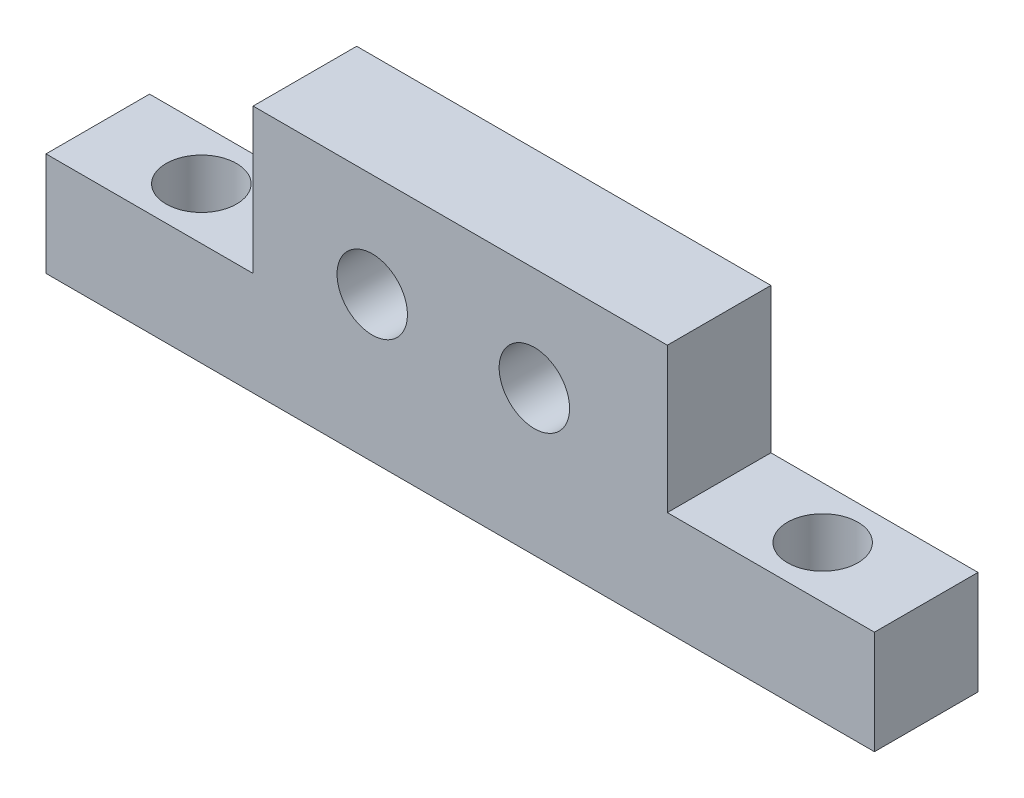
SolidWorks part; units mm, degrees
ref_plane "Plan de face" through (0, 0, 0) normal (0, 0, 1) x (1, 0, 0)
ref_plane "Plan de dessus" through (0, 0, 0) normal (0, 1, 0) x (1, 0, 0)
ref_plane "Plan de droite" through (0, 0, 0) normal (1, 0, 0) x (0, 0, -1)
sketch "Sketch1" plane through (0, 0, 0) normal (0, 0, 1) x (1, 0, 0)
  line L0 (10, -3.5) -> (20, -3.5)
  line L2 (10, -3.5) -> (10, 3.5)
  line L3 (10, 3.5) -> (-10, 3.5)
  line L4 (-10, -3.5) -> (-10, 3.5)
  line L5 (10, -3.5) -> (-10, 3.5) construction
  line L6 (10, 3.5) -> (-10, -3.5) construction
  line L7 (-20, -3.5) -> (-10, -3.5)
  line L8 (-20, -3.5) -> (-20, -8.5)
  line L9 (-20, -8.5) -> (20, -8.5)
  line L10 (20, -3.5) -> (20, -8.5)
  point P0 (0, 0)
  dimension "D1" = 7
  dimension "D2" = 20
  dimension "D3" = 10
  dimension "D4" = 10
  dimension "D5" = 5
extrude "Boss-Extrude1" add sketch "Sketch1" along normal blind 5
hole_wizard "Dégagement M31" positions "Sketch2" profile "Sketch3" hole size "M3" standard "ISO" end condition through all
sketch "Sketch2" plane through (0, 0, 5) normal (0, 0, 1) x (1, 0, 0)
  line L0 (-20, -8.5) -> (20, -8.5) construction
  point P0 (3.58, -1.5)
  point P2 (-4.2483, -1.5)
  dimension "D1" = 7
  dimension "D2" = 7
sketch "Sketch3" plane through (3.58, -1.5, 5) normal (1, 0, 0) x (0, -1, 0)
  line L0 (0, 0) -> (0, 5)
  line L1 (0, 5) -> (1.7, 5)
  line L2 (1.7, 5) -> (1.7, 0)
  line L5 (1.7, 0) -> (0, 0)
  line L11 (0, -6.35) -> (0, 107.95) construction
  dimension "Diamètre du perçage jusqu'au prochain" = 3.4
  dimension "Profondeur du perçage jusqu'au prochain" = 5
hole_wizard "Dégagement M32" positions "Sketch4" profile "Sketch5" hole size "M3" standard "ISO" end condition through all
sketch "Sketch4" plane through (0, -3.5, 0) normal (0, 1, 0) x (1, 0, 0)
  line L0 (20, -5) -> (20, 0) construction
  line L1 (20, -5) -> (10, -5) construction
  line L2 (-10, -5) -> (-20, -5) construction
  line L3 (-20, -5) -> (-20, 0) construction
  point P0 (-15, -2.5)
  point P2 (15, -2.5)
  dimension "D1" = 5
  dimension "D2" = 2.5
  dimension "D3" = 2.5
  dimension "D4" = 5
sketch "Sketch5" plane through (-15, -3.5, 2.5) normal (1, 0, 0) x (0, 0, 1)
  line L0 (0, 0) -> (0, 5)
  line L1 (0, 5) -> (1.7, 5)
  line L2 (1.7, 5) -> (1.7, 0)
  line L5 (1.7, 0) -> (0, 0)
  line L11 (0, -6.35) -> (0, 107.95) construction
  dimension "Diamètre du perçage jusqu'au prochain" = 3.4
  dimension "Profondeur du perçage jusqu'au prochain" = 5
